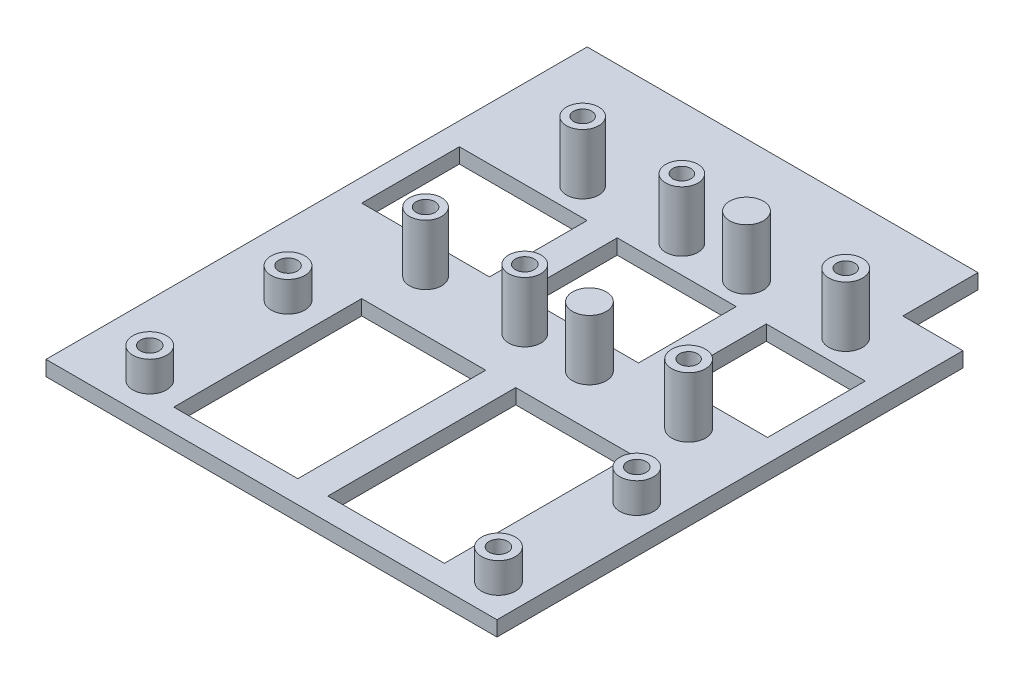
SolidWorks part; units mm, degrees
ref_plane "Front Plane" through (0, 0, 0) normal (0, 0, 1) x (1, 0, 0)
ref_plane "Top Plane" through (0, 0, 0) normal (0, 1, 0) x (1, 0, 0)
ref_plane "Right Plane" through (0, 0, 0) normal (1, 0, 0) x (0, 0, -1)
sketch "Sketch1" plane through (0, 0, 0) normal (0, 1, 0) x (1, 0, 0)
  line L1 (-30, 36) -> (30, 36)
  line L2 (-30, 36) -> (-30, -36)
  line L3 (-30, -36) -> (30, -36)
  line L4 (30, 36) -> (30, -36)
  line L5 (-30, 36) -> (30, -36) construction
  line L6 (-30, -36) -> (30, 36) construction
  point P0 (0, 0)
  dimension "D1" = 72
  dimension "D2" = 60
extrude "Bottom" add sketch "Sketch1" along normal blind 2
sketch "Sketch2" plane through (0, 2, 0) normal (0, 1, 0) x (1, 0, 0)
  line L1 (-23, -10.8) -> (28, -10.8) construction
  line L2 (-23, -10.8) -> (-23, -33.8) construction
  line L3 (-23, -33.8) -> (28, -33.8) construction
  line L4 (28, -10.8) -> (28, -33.8) construction
  line L6 (-30, -36) -> (30, -36) construction
  line L7 (28, -22.3) -> (-23, -22.3) construction
  line L8 (28, -10.8) -> (25.7, -10.8) construction
  line L9 (28, -10.8) -> (28, -13.1) construction
  line L10 (28, -13.1) -> (25.7, -13.1) construction
  line L11 (25.7, -10.8) -> (25.7, -13.1) construction
  line L12 (30, -36) -> (30, 36) construction
  line L14 (2.5, -10.8) -> (2.5, -33.8) construction
  circle A1 centre (25.7, -13.1) radius 2.25
  circle A2 centre (-20.7, -13.1) radius 2.25
  circle A3 centre (25.7, -31.5) radius 2.25
  circle A4 centre (-20.7, -31.5) radius 2.25
  point P26 (-24.7, -31.65)
  dimension "D8" = 4.5
  dimension "D1" = 51
  dimension "D2" = 23
  dimension "D3" = 2
  dimension "D5" = 2.2
  dimension "D6" = 2.3
  dimension "D7" = 2.3
extrude "Pin Locs" add sketch "Sketch2" along normal blind 4
sketch "Sketch5" plane through (0, 6, 0) normal (0, 1, 0) x (1, 0, 0)
  circle A0 centre (-20.7, -31.5) radius 1.25
  circle A1 centre (-20.7, -13.1) radius 1.25
  circle A2 centre (25.7, -13.1) radius 1.25
  circle A3 centre (25.7, -31.5) radius 1.25
  dimension "D1" = 2.5
extrude "Pin Holes" cut sketch "Sketch5" against normal blind 4
sketch "Sketch3" plane through (0, 2, 0) normal (0, 1, 0) x (1, 0, 0)
  line L0 (1.2, -3.5) -> (-16.6, -3.5) construction
  line L1 (23, -3.5) -> (5.2, -3.5) construction
  line L2 (23, -3.5) -> (23, 22) construction
  line L3 (23, 22) -> (5.2, 22) construction
  line L4 (5.2, -3.5) -> (5.2, 22) construction
  line L5 (1.2, -3.5) -> (1.2, 22) construction
  line L6 (1.2, 22) -> (-16.6, 22) construction
  line L7 (-16.6, -3.5) -> (-16.6, 22) construction
  line L8 (30, -36) -> (30, 36) construction
  line L9 (30, 36) -> (-30, 36) construction
  line L10 (14.1, 22) -> (14.1, -3.5) construction
  line L11 (5.2, 9.25) -> (23, 9.25) construction
  line L12 (-7.7, 22) -> (-7.7, -3.5) construction
  line L13 (-16.6, 9.25) -> (1.2, 9.25) construction
  line L14 (-14.3, -1.2) -> (-1.1, -1.2) construction
  line L15 (23, 22) -> (20.7, 22) construction
  line L16 (23, 22) -> (23, 19.7) construction
  line L17 (23, 19.7) -> (20.7, 19.7) construction
  line L18 (20.7, 22) -> (20.7, 19.7) construction
  line L19 (1.2, 22) -> (-1.1, 22) construction
  line L20 (1.2, 22) -> (1.2, 19.7) construction
  line L21 (1.2, 19.7) -> (-1.1, 19.7) construction
  line L22 (-1.1, 22) -> (-1.1, 19.7) construction
  line L23 (7.5, -1.2) -> (20.7, -1.2) construction
  circle A0 centre (20.7, 19.7) radius 2.25
  circle A1 centre (20.7, -1.2) radius 2.25
  circle A2 centre (7.5, -1.2) radius 2.25
  circle A3 centre (7.5, 19.7) radius 2.25
  circle A4 centre (-1.1, 19.7) radius 2.15
  circle A5 centre (-1.1, -1.2) radius 2.15
  circle A6 centre (-14.3, -1.2) radius 2.15
  circle A7 centre (-14.3, 19.7) radius 2.15
  dimension "D10" = 4.5
  dimension "D13" = 4.3
  dimension "D2" = 17.8
  dimension "D3" = 17.8
  dimension "D4" = 25.5
  dimension "D5" = 7
  dimension "D6" = 14
  dimension "D7" = 4
  dimension "D8" = 2.3
  dimension "D9" = 2.3
  dimension "D11" = 2.3
  dimension "D12" = 2.3
extrude "Sensor Pins" add sketch "Sketch3" along normal blind 8
sketch "Sketch6" plane through (0, 10, 0) normal (0, 1, 0) x (1, 0, 0)
  circle A0 centre (-14.3, -1.2) radius 1.25
  circle A1 centre (-1.1, -1.2) radius 1.25
  circle A2 centre (-1.1, 19.7) radius 1.2
  circle A3 centre (-14.3, 19.7) radius 1.2
  circle A6 centre (20.7, -1.2) radius 1.2
  circle A7 centre (20.7, 19.7) radius 1.2
  dimension "D1" = 2.5
extrude "Pin Holes Sensors" cut sketch "Sketch6" against normal blind 4
sketch "Sketch4" plane through (0, 2, 0) normal (0, 1, 0) x (1, 0, 0)
  line L1 (30, 36) -> (22, 36)
  line L2 (30, 36) -> (30, 26)
  line L3 (30, 26) -> (22, 26)
  line L4 (22, 36) -> (22, 26)
  dimension "D1" = 10
  dimension "D2" = 8
extrude "Power Cable" cut sketch "Sketch4" against normal blind 2
sketch "Sketch7" plane through (0, 2, 0) normal (0, 1, 0) x (1, 0, 0)
  line L0 (-30, 36) -> (-30, -36) construction
  line L1 (-16, -8) -> (0.5, -8)
  line L2 (-16, -8) -> (-16, -33)
  line L3 (-16, -33) -> (0.5, -33)
  line L4 (0.5, -8) -> (0.5, -33)
  line L5 (-27, 16) -> (-10, 16)
  line L6 (-27, 16) -> (-27, 3)
  line L7 (-27, 3) -> (-10, 3)
  line L8 (-10, 16) -> (-10, 3)
  line L9 (30, -36) -> (30, 26) construction
  line L10 (-30, -36) -> (30, -36) construction
  line L11 (22, 36) -> (-30, 36) construction
  line L18 (-6, 16) -> (9.834, 16)
  line L19 (-6, 16) -> (-6, 3)
  line L20 (-6, 3) -> (9.834, 3)
  line L21 (9.834, 16) -> (9.834, 3)
  line L22 (13.834, 16) -> (27, 16)
  line L23 (13.834, 16) -> (13.834, 3)
  line L24 (13.834, 3) -> (27, 3)
  line L25 (27, 16) -> (27, 3)
  line L26 (4.5, -8) -> (20, -8)
  line L27 (4.5, -8) -> (4.5, -33)
  line L28 (4.5, -33) -> (20, -33)
  line L29 (20, -8) -> (20, -33)
  dimension "D1" = 14
  dimension "D2" = 29.5
  dimension "D3" = 3
  dimension "D4" = 44
  dimension "D5" = 11
  dimension "D6" = 20
  dimension "D7" = 40
  dimension "D8" = 3
  dimension "D13" = 4
  dimension "D14" = 4
  dimension "D15" = 3
  dimension "D16" = 10
  dimension "D17" = 4
extrude "Cut-Extrude1" cut sketch "Sketch7" against normal blind 2
